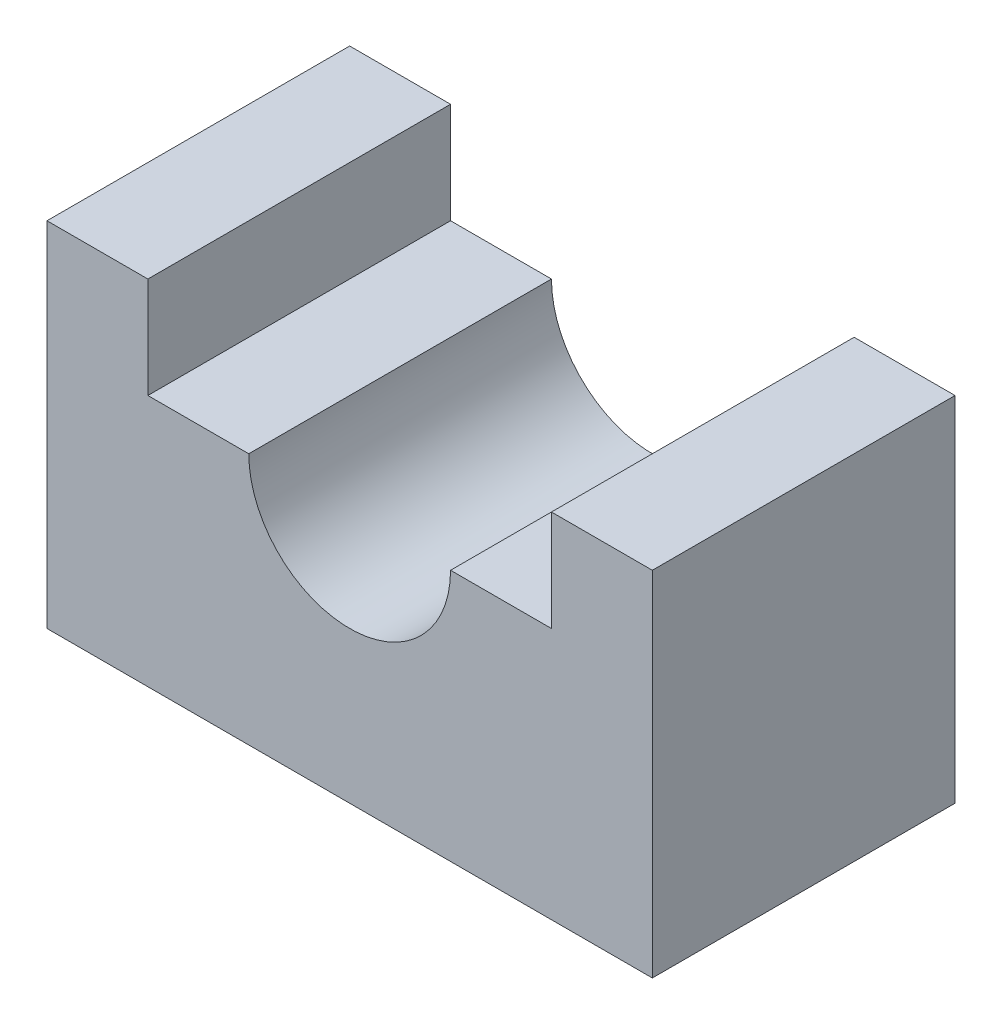
SolidWorks part; units mm, degrees
ref_plane "Front Plane" through (0, 0, 0) normal (0, 0, 1) x (1, 0, 0)
ref_plane "Top Plane" through (0, 0, 0) normal (0, 1, 0) x (1, 0, 0)
ref_plane "Right Plane" through (0, 0, 0) normal (1, 0, 0) x (0, 0, -1)
sketch "Sketch1" plane through (0, 0, 0) normal (0, 0, 1) x (1, 0, 0)
  line L0 (0, 1070) -> (0, 35) construction
  line L1 (0, 0) -> (20537.8213, 0) construction
  line L2 (-20, 35) -> (-20, 25)
  line L3 (-30, 35) -> (-20, 35)
  line L4 (-30, 35) -> (-30, 0)
  line L5 (-30, 0) -> (30, 0)
  line L6 (30, 35) -> (30, 0)
  line L7 (-30, 35) -> (30, 0) construction
  line L8 (-30, 0) -> (30, 35) construction
  line L9 (-20, 25) -> (-10, 25)
  line L10 (10, 25) -> (20, 25)
  line L11 (20, 25) -> (20, 35)
  line L12 (20, 35) -> (30, 35)
  line L13 (0, 17.5) -> (0, -20537.8213) construction
  arc A0 (-10, 25) -> (10, 25) centre (0, 25) ccw
  point P5 (0, 17.5)
  point P15 (0, 0)
  point P20 (0, 0)
  dimension "D4" = 10
  dimension "D1" = 60
  dimension "D2" = 35
  dimension "D3" = 10
extrude "Boss-Extrude1" add sketch "Sketch1" along normal mid plane 30
